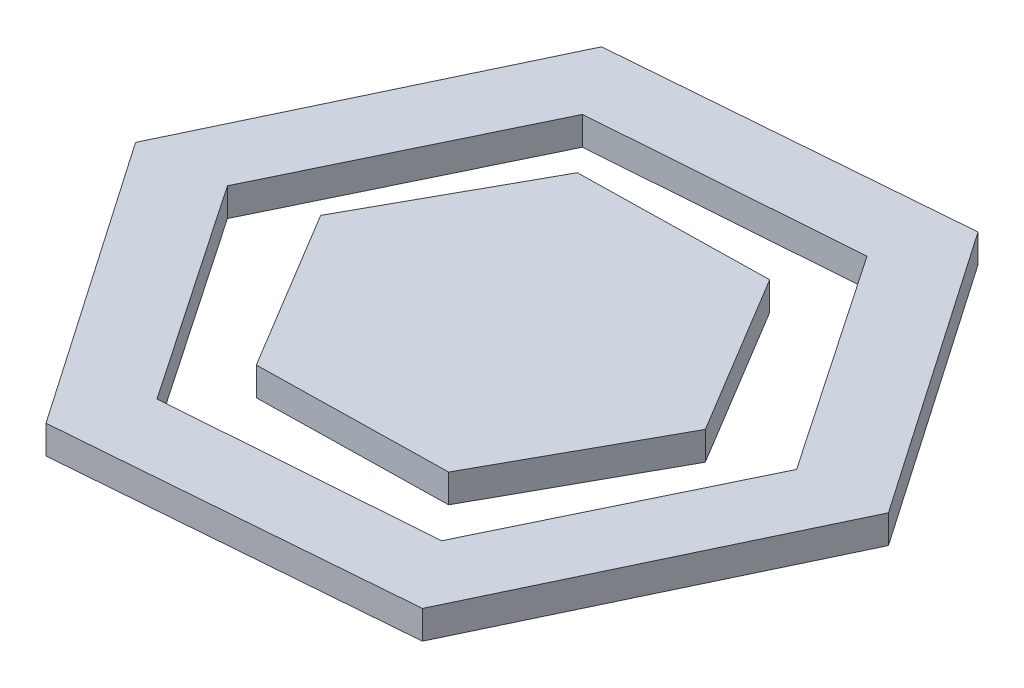
SolidWorks part; units mm, degrees
ref_plane "Front Plane" through (0, 0, 0) normal (0, 0, 1) x (1, 0, 0)
ref_plane "Top Plane" through (0, 0, 0) normal (0, 1, 0) x (1, 0, 0)
ref_plane "Right Plane" through (0, 0, 0) normal (1, 0, 0) x (0, 0, -1)
sketch "Sketch1" plane through (0, 0, 0) normal (0, 1, 0) x (1, 0, 0)
  line L1 (-19.619, 20.2407) -> (-18.0326, 23.5766)
  line L2 (-18.0326, 23.5766) -> (-20.1285, 26.6183)
  line L3 (-20.1285, 26.6183) -> (-23.8106, 26.3242)
  line L4 (-23.8106, 26.3242) -> (-25.3969, 22.9882)
  line L5 (-25.3969, 22.9882) -> (-23.3011, 19.9465)
  line L6 (-23.3011, 19.9465) -> (-19.619, 20.2407)
  line L7 (-20.1364, 20.9603) -> (-18.9146, 23.4883)
  line L8 (-18.9146, 23.4883) -> (-20.493, 25.8104)
  line L9 (-20.493, 25.8104) -> (-23.2932, 25.6045)
  line L10 (-23.2932, 25.6045) -> (-24.515, 23.0766)
  line L11 (-24.515, 23.0766) -> (-22.9366, 20.7545)
  line L12 (-22.9366, 20.7545) -> (-20.1364, 20.9603)
  circle A0 centre (-21.7148, 23.2824) radius 3.199 construction
  circle A1 centre (-21.7148, 23.2824) radius 2.4316 construction
extrude "Boss-Extrude1" add sketch "Sketch1" along normal blind 0.3
sketch "Sketch3" plane through (0, 0, 0) normal (0, 1, 0) x (1, 0, 0)
  line L1 (-20.7281, 21.6266) -> (-19.7627, 23.3724)
  line L2 (-19.7627, 23.3724) -> (-20.792, 25.0814)
  line L3 (-20.792, 25.0814) -> (-22.7867, 25.0445)
  line L4 (-22.7867, 25.0445) -> (-23.7521, 23.2986)
  line L5 (-23.7521, 23.2986) -> (-22.7228, 21.5897)
  line L6 (-22.7228, 21.5897) -> (-20.7281, 21.6266)
  circle A0 centre (-21.7574, 23.3355) radius 1.7277 construction
  point P1 (-23.213, 25.8046)
extrude "Boss-Extrude2" add sketch "Sketch3" along normal blind 0.3 separate body
